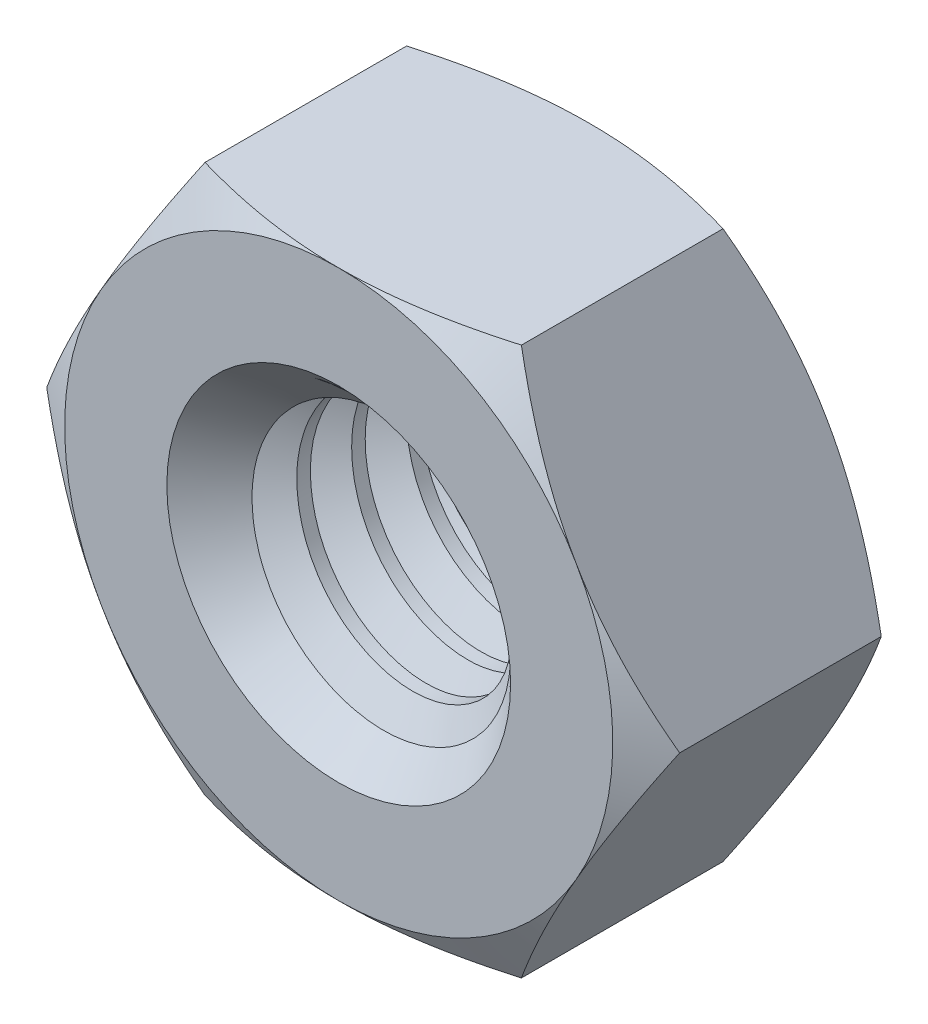
SolidWorks part; units mm, degrees
ref_plane "Front" through (0, 0, 0) normal (0, 0, 1) x (1, 0, 0)
ref_plane "Top" through (0, 0, 0) normal (0, 1, 0) x (1, 0, 0)
ref_plane "Right" through (0, 0, 0) normal (1, 0, 0) x (0, 0, -1)
sketch "Çizim1" plane through (0, 0, 0) normal (0, 0, 1) x (1, 0, 0)
  line L1 (4.0415, 0) -> (2.0207, 3.5)
  line L2 (2.0207, 3.5) -> (-2.0207, 3.5)
  line L3 (-2.0207, 3.5) -> (-4.0415, 0)
  line L4 (-4.0415, 0) -> (-2.0207, -3.5)
  line L5 (-2.0207, -3.5) -> (2.0207, -3.5)
  line L6 (2.0207, -3.5) -> (4.0415, 0)
  circle A0 centre (0, 0) radius 3.5 construction
  dimension "D1" = 7
extrude "Yükseklik-Ekstrüzyon1" add sketch "Çizim1" along normal blind 3.2
sketch "Çizim2" plane through (0, 0, 3.2) normal (0, 0, 1) x (1, 0, 0)
  circle A0 centre (0, 0) radius 3.5
extrude "Kes-Ekstrüzyon1" cut sketch "Çizim2" against normal blind 3.2 draft 60 flip side to cut
sketch "Çizim3" plane through (0, 0, 0) normal (0, 0, -1) x (-1, 0, 0)
  circle A0 centre (0, 0) radius 3.5
extrude "Kes-Ekstrüzyon2" cut sketch "Çizim3" against normal blind 3.2 draft 60 flip side to cut
sketch "Çizim5" plane through (0, 0, 0) normal (0, 0, -1) x (-1, 0, 0)
  circle A0 centre (0, 0) radius 1.545
  dimension "D1" = 3.09
extrude "Kes-Ekstrüzyon3" cut sketch "Çizim5" against normal blind 3.2
chamfer "Pah1" distance 0.65 angle 45 2 edges at (-1.545, 0, 3.2) (-1.545, 0, 0)
sketch "Çizim6" plane through (0, 0, 0) normal (0, 0, -1) x (-1, 0, 0)
  circle A0 centre (0, 0) radius 1.545
curve "Helis/Spiral1" pitch 0.7 height 4 turns 5.7143
ref_plane "Düzlem1" through (-0.3438, -1.5063, 4) normal (0.9724, -0.2219, 0.0719) x (0.0701, -0.016, -0.9974)
sketch "Çizim7" plane through (-0.3438, -1.5063, 4) normal (0.9724, -0.2219, 0.0719) x (0.0701, -0.016, -0.9974)
  line L0 (0.3473, 0.1465) -> (-0.3473, 0.1465)
  line L1 (0, -0.455) -> (0.3473, 0.1465)
  line L3 (-0.3473, 0.1465) -> (0, -0.455)
  line L5 (0.394, 0.2275) -> (0, 0.2275) [skipped]
  circle A0 centre (0, 0) radius 0.2275 construction
  dimension "D1" = 0.455
sweep "Kes-Süpür1" cut profiles "Çizim7" path "Helis/Spiral1"
